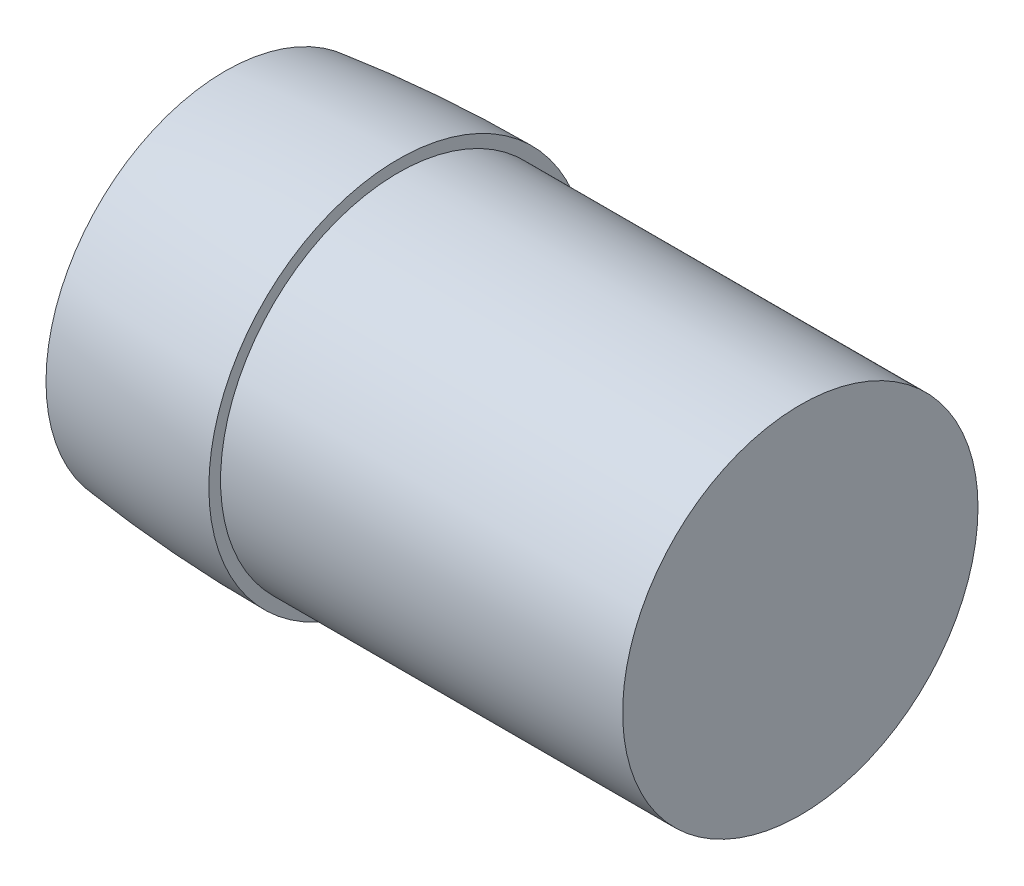
SolidWorks part; units mm, degrees
ref_plane "Front Plane" through (0, 0, 0) normal (0, 0, 1) x (1, 0, 0)
ref_plane "Top Plane" through (0, 0, 0) normal (0, 1, 0) x (1, 0, 0)
ref_plane "Right Plane" through (0, 0, 0) normal (1, 0, 0) x (0, 0, -1)
sketch "Sketch1" plane through (0, 0, 0) normal (0, 0, 1) x (1, 0, 0)
  line L0 (0, 0) -> (0, 316.6744) construction
  line L2 (0, 316.6744) -> (0, 314.1744)
  line L3 (0, 314.1744) -> (86, 314.1744)
  line L4 (86, 314.1744) -> (86, 276.1744)
  line L6 (86, 276.1744) -> (-149.7774, 276.1744) construction
  line L7 (81, 309.1744) -> (81, 276.1744)
  line L8 (-5, 309.1744) -> (81, 309.1744)
  line L9 (-5, 314.1346) -> (-5, 309.1744)
  line L10 (81, 276.1744) -> (86, 276.1744)
  line L12 (-149.7774, 276.1744) -> (-37, 276.1744) construction
  line L13 (-37, 311.9881) -> (-37, 314.5055)
  line L14 (0, 319.1744) -> (0, 314.1744) construction
  arc A1 (-5, 314.1346) -> (-37, 311.9881) centre (0, 0) ccw
  arc A2 (-5, 314.1346) -> (-157.4935, 271.848) centre (0, 0) ccw construction
  arc A3 (-5.0398, 316.6343) -> (-37, 314.5055) centre (0, 0) ccw
  arc A6 (0, 316.6744) -> (-37, 314.5055) centre (0, 0) ccw
  arc A7 (0, 319.1744) -> (-160, 276.1744) centre (0, 0) ccw construction
  arc A9 (-5.0398, 316.6343) -> (-150.9692, 278.372) centre (0, 0) ccw construction
  arc A10 (-5, 314.1346) -> (-149.7774, 276.1744) centre (0, 0) ccw construction
  dimension "D2" = 5
  dimension "D3" = 86
  dimension "D4" = 38
  dimension "D5" = 2.5
revolve "Revolve1" add sketch "Sketch1" angle 360 about L6
